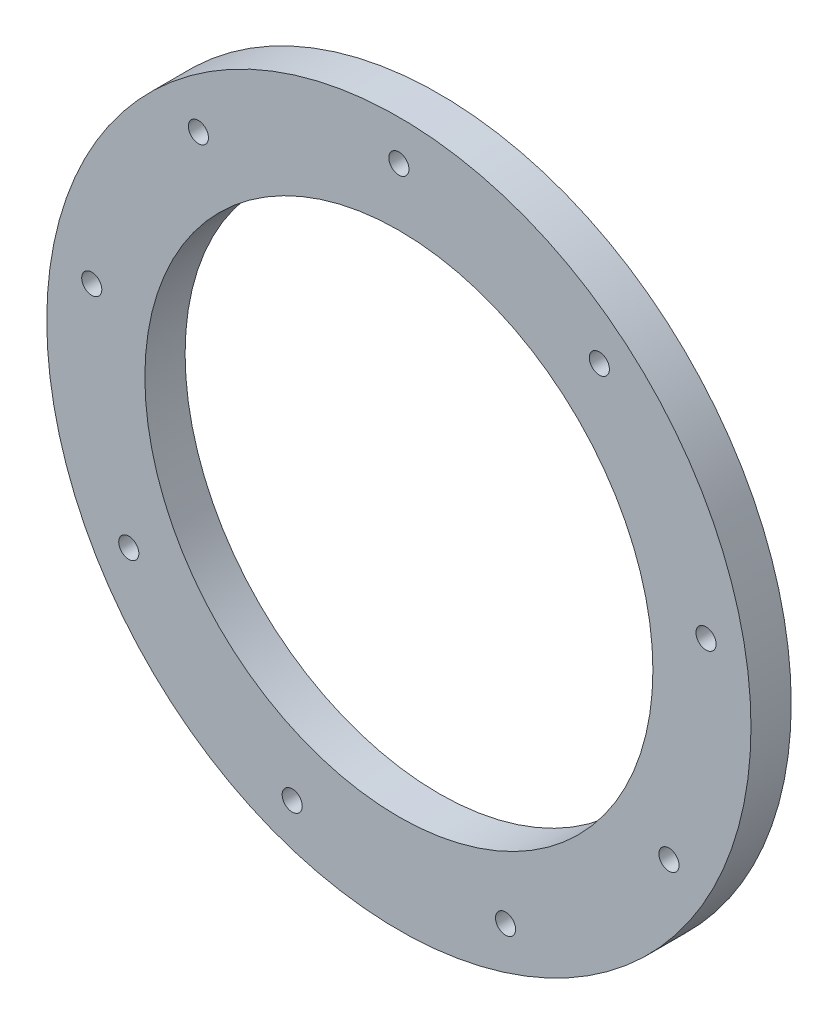
SolidWorks part; units mm, degrees
ref_plane "前视基准面" through (0, 0, 0) normal (0, 0, 1) x (1, 0, 0)
ref_plane "上视基准面" through (0, 0, 0) normal (0, 1, 0) x (1, 0, 0)
ref_plane "右视基准面" through (0, 0, 0) normal (1, 0, 0) x (0, 0, -1)
other "Configuration Table"
sketch "草图2" plane through (0, 0, 0) normal (0, 0, 1) x (1, 0, 0)
  circle A0 centre (0, 0) radius 50.5
  circle A1 centre (0, 0) radius 70
  circle A2 centre (0, 0) radius 62 construction
  circle A3 centre (0, 62) radius 2
  circle A4 centre (39.8528, 47.4948) radius 2
  circle A5 centre (61.0581, 10.7662) radius 2
  circle A6 centre (53.6936, -31) radius 2
  circle A7 centre (21.2052, -58.2609) radius 2
  circle A8 centre (-21.2052, -58.2609) radius 2
  circle A9 centre (-53.6936, -31) radius 2
  circle A10 centre (-61.0581, 10.7662) radius 2
  circle A11 centre (-39.8528, 47.4948) radius 2
  point P25 (0, 0)
  dimension "D1" = 140
  dimension "D2" = 101
  dimension "D3" = 124
  dimension "D4" = 4
  dimension "D5" = 9
extrude "凸台-拉伸1" add sketch "草图2" along normal blind 8
